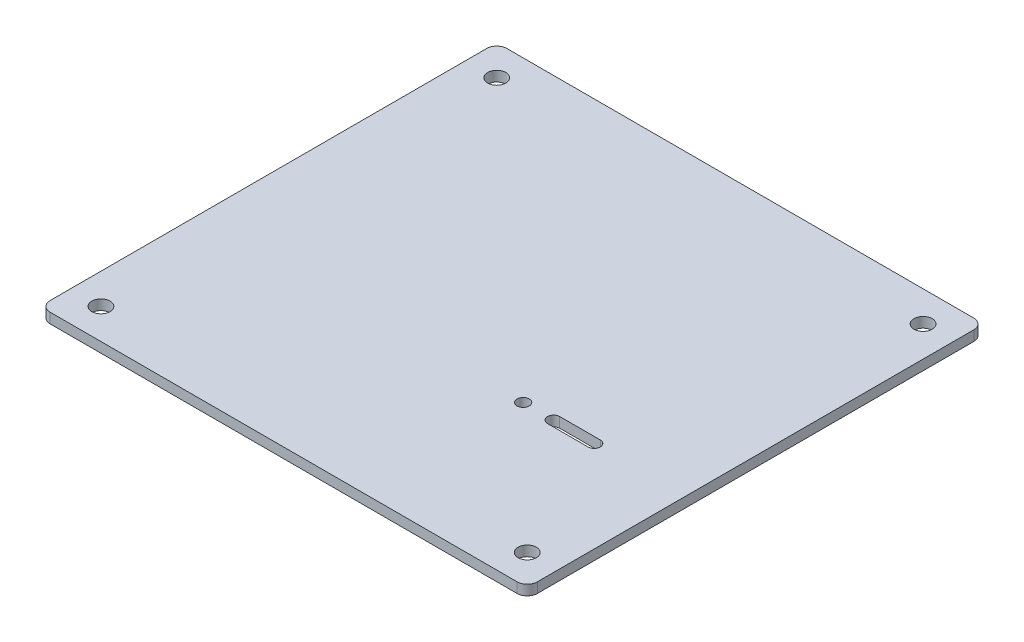
SolidWorks part; units mm, degrees
ref_plane "Front" through (0, 0, 0) normal (0, 0, 1) x (1, 0, 0)
ref_plane "Top" through (0, 0, 0) normal (0, 1, 0) x (1, 0, 0)
ref_plane "Right" through (0, 0, 0) normal (1, 0, 0) x (0, 0, -1)
sketch "Sketch1" plane through (0, 0, 0) normal (0, 1, 0) x (1, 0, 0)
  line L1 (0, 0) -> (350, 0)
  line L2 (0, 0) -> (0, 200)
  line L3 (0, 200) -> (350, 200)
  line L4 (350, 0) -> (350, 200)
  dimension "D1" = 200
  dimension "D2" = 350
extrude "Boss-Extrude1" add sketch "Sketch1" along normal blind 5
ref_plane "Plane1" through (0, 0, -100) normal (0, 0, 1) x (1, 0, 0)
hole_wizard "M4 Clearance Hole2" positions "Sketch5" profile "Sketch6" hole size "M4" standard "ISO"
sketch "Sketch5" plane through (0, 5, 0) normal (0, 1, 0) x (1, 0, 0)
  line L0 (0, 100) -> (350, 100) construction
  line L1 (0, 200) -> (0, 0) construction
  line L2 (350, 0) -> (350, 200) construction
  circle A0 centre (279.727, 100) radius 23.5 construction
  point P11 (279.727, 123.5)
  point P13 (303.227, 100)
  point P15 (256.227, 100)
  point P17 (279.727, 76.5)
  dimension "D1" = 47
sketch "Sketch6" plane through (279.727, 5, -76.5) normal (1, 0, 0) x (0, 0, 1)
  line L0 (0, 0) -> (0, 11.3519)
  line L1 (0, 11.3519) -> (2.25, 10)
  line L2 (2.25, 10) -> (2.25, 0)
  line L5 (2.25, 0) -> (0, 0)
  line L10 (0, 11.3519) -> (-2.25, 10) construction
  line L11 (0, -6.35) -> (0, 107.95) construction
  dimension "Hole Dia." = 4.5
  dimension "Hole Depth" = 10
  dimension "Drill Angle" = 118
sketch "Sketch7" plane through (0, 5, 0) normal (0, 1, 0) x (1, 0, 0)
  line L0 (0, 100) -> (350, 100) construction
  line L1 (0, 200) -> (0, 0) construction
  line L2 (350, 0) -> (350, 200) construction
  line L3 (0, 10) -> (350, 10) construction
  line L5 (40, 10) -> (390, 10) construction
  line L6 (20, 10) -> (40, 10)
  line L7 (20, 10) -> (20, 5)
  line L8 (20, 5) -> (40, 5)
  line L9 (40, 10) -> (40, 5)
  line L10 (60, 10) -> (60, 5)
  line L11 (60, 10) -> (80, 10)
  line L12 (80, 10) -> (80, 5)
  line L13 (60, 5) -> (80, 5)
  line L14 (80, 10) -> (430, 10) construction
  line L15 (100, 10) -> (100, 5)
  line L16 (100, 10) -> (120, 10)
  line L17 (120, 10) -> (120, 5)
  line L18 (100, 5) -> (120, 5)
  line L19 (120, 10) -> (470, 10) construction
  line L20 (140, 10) -> (140, 5)
  line L21 (140, 10) -> (160, 10)
  line L22 (160, 10) -> (160, 5)
  line L23 (140, 5) -> (160, 5)
  line L24 (160, 10) -> (510, 10) construction
  line L25 (180, 10) -> (180, 5)
  line L26 (180, 10) -> (200, 10)
  line L27 (200, 10) -> (200, 5)
  line L28 (180, 5) -> (200, 5)
  line L30 (0, 0) -> (350, 0) construction
  dimension "D1" = 10
  dimension "D2" = 5
  dimension "D3" = 20
  dimension "D4" = 20
  dimension "D5" = 5
extrude "Slots" [suppressed] cut sketch "Sketch7" against normal through all
sketch "Sketch8" plane through (0, 5, 0) normal (0, 1, 0) x (1, 0, 0)
  line L0 (174.9992, 78) -> (194.9992, 78) construction
  line L1 (174.9992, 81) -> (194.9992, 81)
  line L2 (174.9992, 75) -> (194.9992, 75)
  line L3 (169.9992, 48) -> (169.9992, 150) construction
  line L4 (184.9992, 78) -> (145.7248, 78) construction
  arc A0 (174.9992, 81) -> (174.9992, 75) centre (174.9992, 78) ccw
  arc A1 (194.9992, 75) -> (194.9992, 81) centre (194.9992, 78) ccw
  circle A2 centre (169.9992, 150) radius 4.8 construction
  circle A3 centre (159.9992, 78) radius 3
  point P2 (184.9992, 78)
  dimension "D1" = 3
  dimension "D5" = 6
  dimension "D6" = 10
  dimension "D2" = 20
  dimension "D3" = 30
  dimension "D4" = 5
extrude "Cut-Extrude2" cut sketch "Sketch8" against normal through all
sketch "Sketch9" plane through (0, 5, 0) normal (0, 1, 0) x (1, 0, 0)
  line L0 (250, 200) -> (350, 100)
  line L1 (350, 200) -> (0, 200) construction
  line L2 (350, 0) -> (350, 200) construction
  line L3 (350, 100) -> (350, 200)
  line L4 (350, 200) -> (250, 200)
  dimension "D1" = 100
extrude "Cut-Extrude3" [suppressed] cut sketch "Sketch9" against normal blind 122
mirror "Mirror3" [suppressed] about plane through (0, 0, -100) normal (0, 0, 1)
fillet "Fillet1" [suppressed] radius 10
fillet "Fillet2" [suppressed] radius 5
sketch "Sketch10" plane through (0, 5, 0) normal (0, 1, 0) x (1, 0, 0)
  line L0 (0, 0) -> (350, 0) construction
  line L1 (350, 200) -> (240, 200)
  line L2 (350, 200) -> (350, 0)
  line L3 (350, 0) -> (240, 0)
  line L4 (240, 200) -> (240, 0)
  line L5 (0, 200) -> (0, 0) construction
  dimension "D1" = 240
extrude "Cut-Extrude4" cut sketch "Sketch10" against normal through all
sketch "Sketch11" plane through (0, 5, 0) normal (0, 1, 0) x (1, 0, 0)
  line L1 (240, 200) -> (0, 200)
  line L2 (240, 200) -> (240, 225)
  line L3 (240, 225) -> (0, 225)
  line L4 (0, 200) -> (0, 225)
  dimension "D1" = 25
extrude "Boss-Extrude2" add sketch "Sketch11" against normal up to surface (5 mm away) up to face at (120, 0, -100)
ref_plane "Plane2" through (0, 0, -112.5) normal (0, 0, 1) x (1, 0, 0)
mirror "Mirror1" [suppressed] about plane through (0, 0, -112.5) normal (0, 0, 1)
hole_wizard "M8 Clearance Hole1" positions "Sketch12" profile "Sketch13" hole size "M8" standard "ISO" end condition through all
sketch "Sketch12" plane through (0, 5, 0) normal (0, 1, 0) x (1, 0, 0)
  line L0 (0, 0) -> (240, 0) construction
  line L1 (0, 225) -> (0, 0) construction
  line L2 (0, 112.5) -> (240, 112.5) construction
  line L3 (240, 225) -> (240, 0) construction
  line L5 (120, 225) -> (120, 0) construction
  line L6 (240, 225) -> (0, 225) construction
  point P0 (15, 15)
  point P19 (225, 15)
  point P20 (225, 210)
  point P21 (15, 210)
  dimension "D1" = 15
  dimension "D2" = 15
sketch "Sketch13" plane through (15, 5, -15) normal (1, 0, 0) x (0, 0, 1)
  line L0 (0, 0) -> (0, 5)
  line L1 (0, 5) -> (4.5, 5)
  line L2 (4.5, 5) -> (4.5, 0)
  line L5 (4.5, 0) -> (0, 0)
  line L11 (0, -6.35) -> (0, 107.95) construction
  dimension "Thru Hole Dia." = 9
  dimension "Thru Hole Depth" = 5
fillet "Fillet3" radius 5 4 edges at (0, 2.5, -225) (240, 2.5, -225) (240, 2.5, 0) (0, 2.5, 0)
